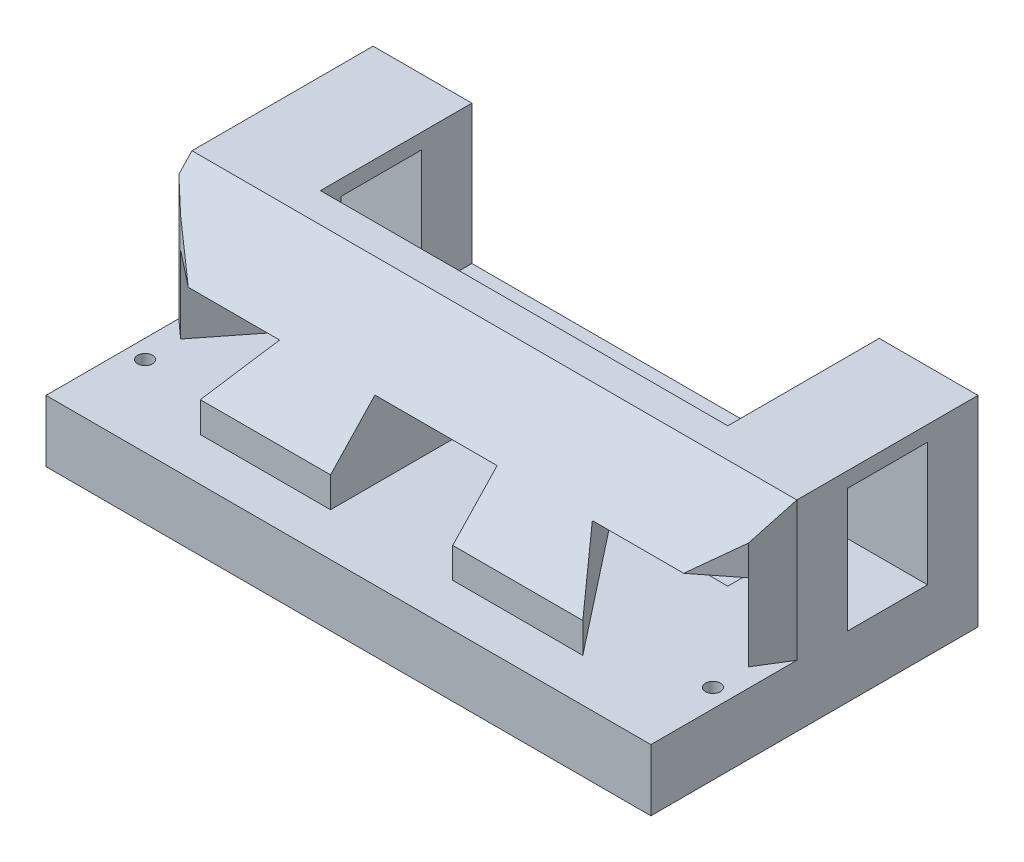
SolidWorks part; units mm, degrees
ref_plane "Alzado" through (0, 0, 0) normal (0, 0, 1) x (1, 0, 0)
ref_plane "Planta" through (0, 0, 0) normal (0, 1, 0) x (1, 0, 0)
ref_plane "Vista lateral" through (0, 0, 0) normal (1, 0, 0) x (0, 0, -1)
sketch "Croquis1" plane through (0, 0, 0) normal (0, 1, 0) x (1, 0, 0)
  line L1 (-39.0284, 19.1926) -> (58.9716, 19.1926)
  line L2 (-39.0284, 19.1926) -> (-39.0284, -33.8074)
  line L3 (-39.0284, -33.8074) -> (58.9716, -33.8074)
  line L4 (58.9716, 19.1926) -> (58.9716, -33.8074)
  dimension "D1" = 98
  dimension "D2" = 53
extrude "Saliente-Extruir1" add sketch "Croquis1" along normal blind 35
sketch "Croquis2" plane through (0, 35, 0) normal (0, 1, 0) x (1, 0, 0)
  line L0 (9.9716, -26.8074) -> (9.9716, 19.1926) construction
  line L2 (58.9716, 19.1926) -> (-39.0284, 19.1926) construction
  line L4 (9.9716, -26.8074) -> (40.9428, -26.8074) construction
  line L6 (9.9716, -26.8074) -> (-21.0287, -26.8074) construction
  line L7 (-39.0284, 19.1926) -> (-39.0284, -33.8074) construction
  line L8 (58.9716, 19.1926) -> (58.9716, -10.1556) construction
  line L9 (9.9716, -26.8074) -> (-0.0284, -26.8074)
  line L10 (9.9716, -26.8074) -> (9.9716, -12.8074)
  line L11 (9.9716, -12.8074) -> (-0.0284, -12.8074)
  line L12 (-0.0284, -26.8074) -> (-0.0284, -12.8074)
  line L13 (9.9716, -26.8074) -> (19.9716, -26.8074)
  line L14 (9.9716, -26.8074) -> (9.9716, -12.8074)
  line L15 (9.9716, -12.8074) -> (19.9716, -12.8074)
  line L16 (19.9716, -26.8074) -> (19.9716, -12.8074)
  line L18 (58.9716, -5.3074) -> (58.9716, -10.1556)
  line L21 (-39.0284, 19.1926) -> (-39.0284, -7.3074) construction
  line L22 (-39.0284, -7.3074) -> (-39.0284, -12.284) construction
  line L25 (-14.5284, -26.8074) -> (-21.0287, -26.8074) construction
  line L27 (-35.2033, -20.1019) -> (-36.0284, -19.4452) construction
  line L28 (25.4572, -26.8074) -> (40.9428, -26.8074) construction
  line L29 (54.9293, -20.6098) -> (56.1171, -19.7128) construction
  line L30 (58.9716, -10.1556) -> (58.9716, -5.3074) construction
  line L32 (-36.0284, -16.8165) -> (-36.0284, -16.6028)
  line L33 (-36.0284, -16.8165) -> (-36.0284, -16.6028) construction
  line L34 (-36.0284, -15.0038) -> (-36.0284, 19.1926) construction
  line L35 (-39.0284, -12.284) -> (-39.0284, 19.1926)
  line L36 (55.9716, -15.0038) -> (55.9716, 19.1926) construction
  line L37 (-36.0284, -19.7027) -> (-36.0284, -19.4452) construction
  line L38 (-36.0284, -15.0038) -> (55.9716, -15.0038) construction
  line L39 (-36.0284, -15.0038) -> (-21.0287, -26.8074)
  line L40 (55.9716, -15.0038) -> (40.9428, -26.8074)
  line L43 (-36.0284, -15.0038) -> (-39.0284, -12.284)
  line L44 (55.9716, -15.0038) -> (58.9716, -10.1556)
  line L45 (-21.0287, -26.8074) -> (40.9428, -26.8074)
  line L46 (-39.0284, 19.1926) -> (9.9716, 19.1926)
  line L47 (9.9716, 19.1926) -> (58.9716, 19.1926)
  line L48 (58.9716, 19.1926) -> (58.9716, -5.3074)
  circle A0 centre (55.9716, -20.7551) radius 1.0524
  circle A1 centre (-36.0284, -20.7551) radius 1.0524
  dimension "D1" = 3
  dimension "D2" = 10
  dimension "D3" = 10
  dimension "D4" = 14
extrude "Cortar-Extruir1" cut sketch "Croquis2" against normal blind 25
sketch "Croquis4" plane through (0, 35, 0) normal (0, 1, 0) x (1, 0, 0)
  circle A0 centre (-36.0284, -20.7551) radius 1.21
  point P0 (-36.0284, -20.7551)
  dimension "D1" = 2.42
extrude "Cortar-Extruir2" cut sketch "Croquis4" against normal through all
sketch "Croquis5" plane through (0, 35, 0) normal (0, 1, 0) x (1, 0, 0)
  circle A0 centre (55.9716, -20.7551) radius 1.21
  point P0 (55.9716, -20.7551)
  dimension "D1" = 2.42
extrude "Cortar-Extruir3" cut sketch "Croquis5" against normal through all
sketch "Croquis6" plane through (-21.0699, 0, 26.775) normal (-0.6184, 0, 0.7859) x (0.7859, 0, 0.6184)
  line L0 (0.0525, 10) -> (0.0525, 35) construction
  line L1 (-19.0347, 10) -> (0.0525, 10)
  line L2 (-19.0347, 10) -> (-19.0347, 22.5)
  line L3 (-19.0347, 22.5) -> (0.0525, 22.5)
  line L4 (0.0525, 10) -> (0.0525, 22.5)
  dimension "D1" = 19.0871
  dimension "D2" = 12.5
extrude "Cortar-Extruir4" cut sketch "Croquis6" against normal through all
sketch "Croquis7" plane through (28.6424, 0, 36.4683) normal (0.6177, 0, 0.7864) x (0.7864, 0, -0.6177)
  line L0 (34.7506, 10) -> (34.7506, 35) construction
  line L1 (15.6407, 10) -> (34.7506, 10)
  line L2 (15.6407, 10) -> (15.6407, 22.5)
  line L3 (15.6407, 22.5) -> (34.7506, 22.5)
  line L4 (34.7506, 10) -> (34.7506, 22.5)
  dimension "D1" = 12.5
extrude "Cortar-Extruir5" cut sketch "Croquis7" against normal through all
sketch "Croquis8" plane through (0, 0, 26.8074) normal (0, 0, 1) x (1, 0, 0)
  line L0 (9.9571, 35) -> (9.965, 22.5) construction
  line L1 (-21.0287, 35) -> (40.9428, 35) construction
  line L2 (-39.0284, 10) -> (58.9716, 10) construction
  line L4 (9.9716, 10) -> (0.0716, 10)
  line L6 (9.9716, 22.5) -> (0.0716, 22.5)
  line L7 (0.0716, 10) -> (0.0716, 22.5)
  line L8 (9.9716, 10) -> (19.8716, 10)
  line L10 (9.9716, 22.5) -> (19.8716, 22.5)
  line L11 (19.8716, 10) -> (19.8716, 22.5)
  dimension "D1" = 9.9
  dimension "D2" = 9.9
  dimension "D3" = 12.5
extrude "Cortar-Extruir6" cut sketch "Croquis8" against normal through all
sketch "Croquis9" plane through (0, 35, 0) normal (0, 1, 0) x (1, 0, 0)
  line L3 (9.9716, 15.1926) -> (42.9716, 15.1926)
  line L5 (9.9716, -5.3474) -> (42.9716, -5.3474)
  line L6 (42.9716, 15.1926) -> (42.9716, -5.3474)
  line L7 (9.9716, 15.1926) -> (-23.0284, 15.1926)
  line L9 (9.9716, -5.3474) -> (-23.0284, -5.3474)
  line L10 (-23.0284, 15.1926) -> (-23.0284, -5.3474)
  dimension "D2" = 33
  dimension "D3" = 33
  dimension "D4" = 20.54
extrude "Cortar-Extruir7" cut sketch "Croquis9" against normal blind 30
sketch "Croquis10" plane through (58.9716, 0, 0) normal (1, 0, 0) x (0, 0, -1)
  line L0 (-10.1556, 10) -> (19.1926, 10) construction
  line L2 (4.5185, 10) -> (11.0185, 10)
  line L4 (4.5185, 30.02) -> (11.0185, 30.02)
  line L5 (11.0185, 10) -> (11.0185, 30.02)
  line L6 (4.5185, 10) -> (-1.9815, 10)
  line L8 (4.5185, 30.02) -> (-1.9815, 30.02)
  line L9 (-1.9815, 10) -> (-1.9815, 30.02)
  dimension "D1" = 29.3482
  dimension "D2" = 6.5
  dimension "D3" = 6.5
  dimension "D4" = 20.02
extrude "Cortar-Extruir8" cut sketch "Croquis10" against normal through all
sketch "Croquis11" plane through (0, 0, -19.1926) normal (0, 0, -1) x (-1, 0, 0)
  line L2 (-58.9716, 35) -> (39.0284, 35) construction
  line L4 (-9.9716, 35) -> (23.0284, 35)
  line L6 (-9.9716, 10) -> (23.0284, 10)
  line L7 (23.0284, 35) -> (23.0284, 10)
  line L8 (-9.9716, 35) -> (-42.9716, 35)
  line L10 (-9.9716, 10) -> (-42.9716, 10)
  line L11 (-42.9716, 35) -> (-42.9716, 10)
  dimension "D1" = 33
  dimension "D2" = 33
extrude "Cortar-Extruir9" cut sketch "Croquis11" against normal blind 24
sketch "Croquis12" plane through (0, 35, 0) normal (0, 1, 0) x (1, 0, 0)
  line L1 (-42.0776, 21.1129) -> (65.5909, 21.1129)
  line L2 (-42.0776, 21.1129) -> (-42.0776, -36.8552)
  line L3 (-42.0776, -36.8552) -> (65.5909, -36.8552)
  line L4 (65.5909, 21.1129) -> (65.5909, -36.8552)
extrude "Cortar-Extruir10" cut sketch "Croquis12" against normal blind 2.5
sketch "Croquis13" plane through (58.9716, 0, 0) normal (1, 0, 0) x (0, 0, -1)
  line L2 (-33.8074, 7.5) -> (-33.8074, 10)
  line L3 (-33.8074, 10) -> (-33.8074, 7.5)
  line L4 (-33.8074, 7.5) -> (-10.1556, 32.5)
  line L5 (-10.1556, 32.5) -> (-33.8074, 32.5)
  line L6 (-33.8074, 32.5) -> (-33.8074, 7.5)
  line M7 (-10.1556, 10) -> (-33.8074, 10)
extrude "Cortar-Extruir11" cut sketch "Croquis13" against normal through all contours L5 L6 L4 M7
sketch "Croquis15" plane through (0, 0, 0) normal (0, -1, 0) x (1, 0, 0)
  line L0 (55.6416, 25.3974) -> (-35.6984, 25.3974) construction
  line L1 (-39.0284, 33.8074) -> (-35.6984, 33.8074)
  line L2 (-39.0284, 33.8074) -> (-39.0284, 25.3974)
  line L3 (-39.0284, 25.3974) -> (-35.6984, 25.3974)
  line L4 (-35.6984, 33.8074) -> (-35.6984, 25.3974)
  line L5 (58.9716, 33.8074) -> (55.6416, 33.8074)
  line L6 (58.9716, 33.8074) -> (58.9716, 25.3974)
  line L7 (58.9716, 25.3974) -> (55.6416, 25.3974)
  line L8 (55.6416, 33.8074) -> (55.6416, 25.3974)
  dimension "D1" = 3.33
  dimension "D2" = 3.33
  dimension "D3" = 8.41
  dimension "D4" = 8.41
